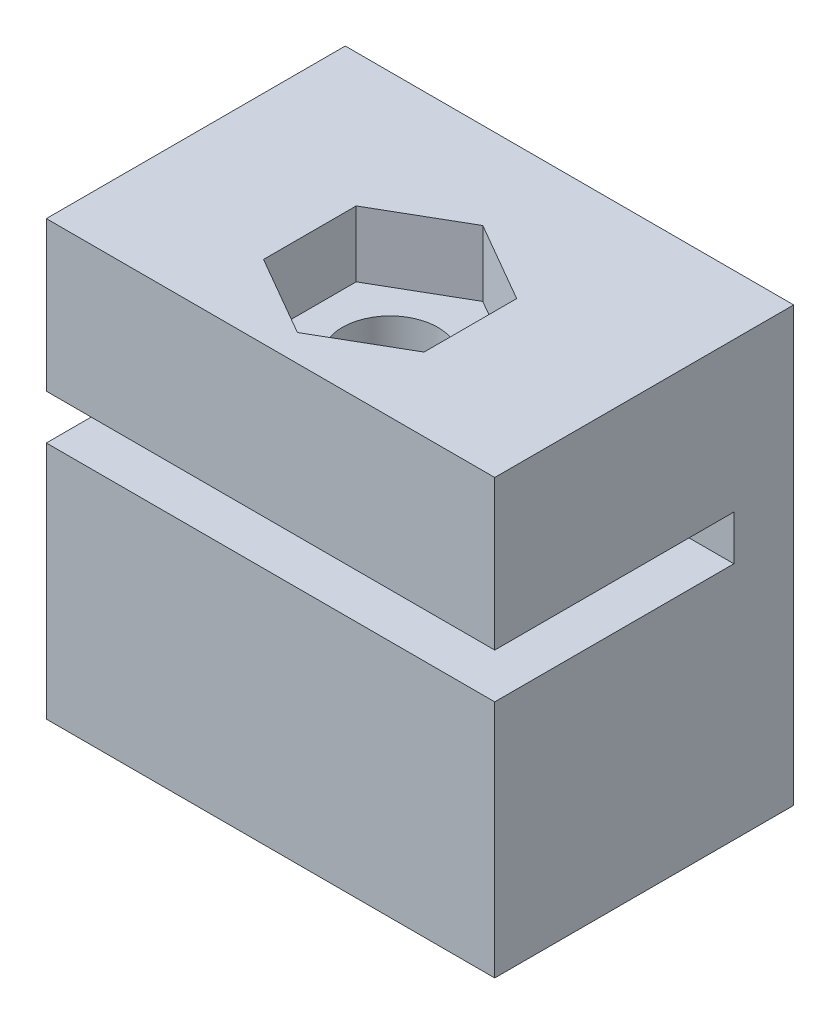
SolidWorks part; units mm, degrees
ref_plane "Front Plane" through (0, 0, 0) normal (0, 0, 1) x (1, 0, 0)
ref_plane "Top Plane" through (0, 0, 0) normal (0, 1, 0) x (1, 0, 0)
ref_plane "Right Plane" through (0, 0, 0) normal (1, 0, 0) x (0, 0, -1)
sketch "Sketch1" plane through (0, 0, 0) normal (0, 1, 0) x (1, 0, 0)
  line L1 (-7.5, 5) -> (7.5, 5)
  line L2 (-7.5, 5) -> (-7.5, -5)
  line L3 (-7.5, -5) -> (7.5, -5)
  line L4 (7.5, 5) -> (7.5, -5)
  line L5 (-7.5, 5) -> (7.5, -5) construction
  line L6 (-7.5, -5) -> (7.5, 5) construction
  point P0 (0, 0)
  dimension "D1" = 15
  dimension "D2" = 10
extrude "base" add sketch "Sketch1" along normal blind 8
sketch "Sketch3" plane through (0, 8, 0) normal (0, 1, 0) x (1, 0, 0)
  line L0 (-5.9962, -5) -> (5.9962, -5)
  line L1 (-7.5, -5) -> (7.5, -5) construction
  line L3 (-5.9962, -5) -> (5.9962, -5)
  line L4 (-5.9962, -5) -> (-5.9962, 3)
  line L5 (-5.9962, 3) -> (5.9962, 3)
  line L6 (5.9962, -5) -> (5.9962, 3)
  line L7 (-7.5, 5) -> (7.5, 5)
  line L8 (-7.5, 5) -> (-7.5, -5)
  line L9 (-7.5, -5) -> (7.5, -5)
  line L10 (7.5, 5) -> (7.5, -5)
  line L11 (-7.5, 5) -> (7.5, 5)
  line L12 (-7.5, 5) -> (-7.5, 3)
  line L13 (-7.5, 3) -> (7.5, 3)
  line L14 (7.5, 5) -> (7.5, 3)
  point P5 (0, -5)
  line M14 (7.5, 5) -> (-7.5, 5)
  line M15 (-7.5, 5) -> (-7.5, -5)
  dimension "D1" = 8
extrude "spacer" add sketch "Sketch3" along normal blind 1.5 contours L13 L5 L10 M15 M14
sketch "Sketch4" plane through (0, 9.5, 0) normal (0, 1, 0) x (1, 0, 0)
  line L1 (-7.5, 5) -> (7.5, 5)
  line L2 (-7.5, 5) -> (-7.5, -5)
  line L3 (-7.5, -5) -> (7.5, -5)
  line L4 (7.5, 5) -> (7.5, -5)
  dimension "D1" = 10
extrude "top" add sketch "Sketch4" along normal blind 5
sketch "Sketch5" plane through (0, 14.5, 0) normal (0, 1, 0) x (1, 0, 0)
  line L0 (-6.0022, -5) -> (6.0022, -5)
  line L1 (-7.5, -5) -> (7.5, -5) construction
  line L3 (-6.0022, -5) -> (6.0022, -5)
  line L4 (-6.0022, -5) -> (-6.0022, 3)
  line L5 (-6.0022, 3) -> (6.0022, 3)
  line L6 (6.0022, -5) -> (6.0022, 3)
  circle A0 centre (0, -1) radius 1.6
  point P5 (0, -5)
  dimension "D2" = 3.2
  dimension "D1" = 8
extrude "bore" cut sketch "Sketch5" against normal through all contours A0
sketch "Sketch6" plane through (0, 14.5, 0) normal (0, 1, 0) x (1, 0, 0)
  line L1 (0, -4.1) -> (2.6847, -2.55)
  line L2 (2.6847, -2.55) -> (2.6847, 0.55)
  line L3 (2.6847, 0.55) -> (0, 2.1)
  line L4 (0, 2.1) -> (-2.6847, 0.55)
  line L5 (-2.6847, 0.55) -> (-2.6847, -2.55)
  line L6 (-2.6847, -2.55) -> (0, -4.1)
  circle A0 centre (0, -1) radius 2.6847 construction
  dimension "D1" = 6.2
extrude "nut" cut sketch "Sketch6" against normal blind 2.2 contours L1 L2 L3 L4 L5 L6
